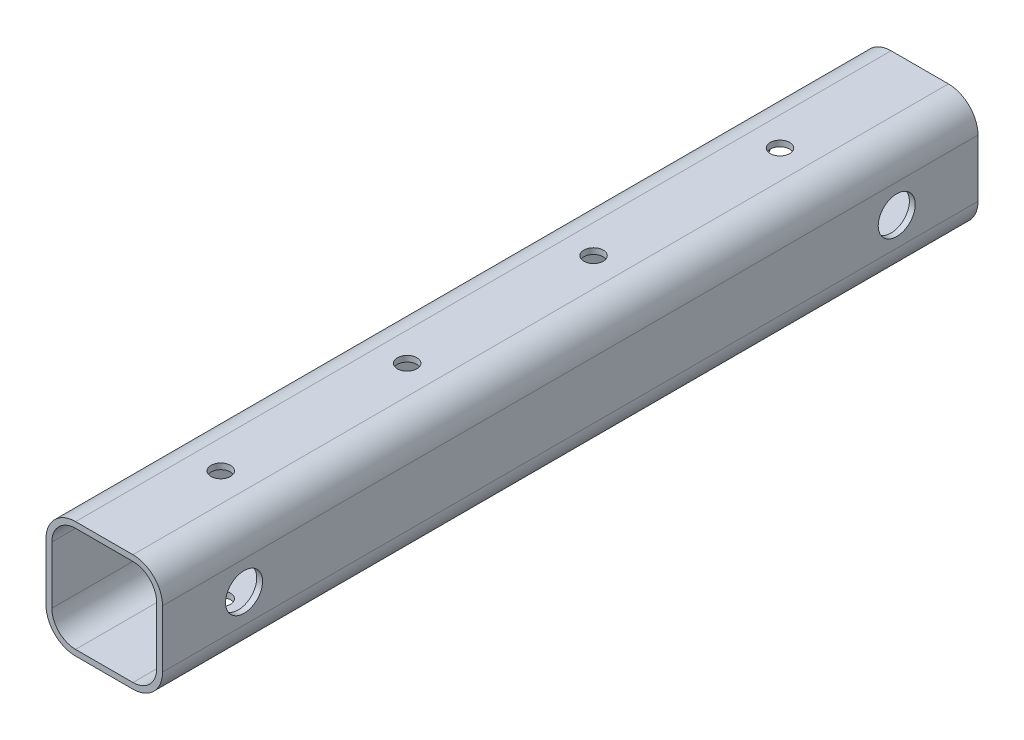
SolidWorks part; units mm, degrees
ref_plane "Alzado" through (0, 0, 0) normal (0, 0, 1) x (1, 0, 0)
ref_plane "Planta" through (0, 0, 0) normal (0, 1, 0) x (1, 0, 0)
ref_plane "Vista lateral" through (0, 0, 0) normal (1, 0, 0) x (0, 0, -1)
sketch "Sketch2" plane through (0, 0, 0) normal (1, 0, 0) x (0, 0, -1)
  line L0 (0, 0) -> (350, 0)
  dimension "D1" = 350
other "Square tube 2 X 2 X 0.25(1)"
ref_plane "Plane1" through (0, 0, 0) normal (0, 0, -1) x (0, 1, 0)
sketch "Sketch15" plane through (0, 0, 0) normal (0, 0, -1) x (0, 1, 0)
  line L0 (-12.3, -22.5) -> (12.3, -22.5)
  line L1 (-22.5, -12.3) -> (-22.5, 12.3)
  line L2 (12.3, 22.5) -> (-12.3, 22.5)
  line L3 (22.5, 12.3) -> (22.5, -12.3)
  line L4 (-12.3, -25) -> (12.3, -25)
  line L5 (-25, -12.3) -> (-25, 12.3)
  line L6 (12.3, 25) -> (-12.3, 25)
  line L7 (25, 12.3) -> (25, -12.3)
  line L8 (0, 0) -> (22.5, 0) construction
  line L9 (0, 0) -> (0, 22.5) construction
  arc A0 (25, 12.3) -> (12.3, 25) centre (12.3, 12.3) ccw
  arc A1 (12.3, -25) -> (25, -12.3) centre (12.3, -12.3) ccw
  arc A2 (-25, -12.3) -> (-12.3, -25) centre (-12.3, -12.3) ccw
  arc A3 (-12.3, 25) -> (-25, 12.3) centre (-12.3, 12.3) ccw
  arc A4 (-12.3, 22.5) -> (-22.5, 12.3) centre (-12.3, 12.3) ccw
  arc A5 (22.5, 12.3) -> (12.3, 22.5) centre (12.3, 12.3) ccw
  arc A6 (12.3, -22.5) -> (22.5, -12.3) centre (12.3, -12.3) ccw
  arc A7 (-22.5, -12.3) -> (-12.3, -22.5) centre (-12.3, -12.3) ccw
  point P3 (0, 25)
  point P4 (25, 0)
  point P5 (0, -25)
  point P6 (-25, 0)
  point P7 (-25, 25)
  point P8 (-25, -25)
  point P33 (0, 0)
  point P35 (25, -25)
  point P36 (25, 25)
  point P37 (0, 0)
  dimension "D1" = 12.7
  dimension "Thickness" = 2.5
  dimension "V_leg" = 50
sketch "Sketch16" plane through (-25, 0, 0) normal (-1, 0, 0) x (0, 0, 1)
  line L0 (0, 25) -> (-50.8, 25)
  line L1 (-50.8, 25) -> (-50.8, -25)
  line L2 (-50.8, -25) -> (0, -25)
  line L3 (0, -25) -> (0, 25)
  line L4 (0, 0) -> (-350, 0) construction
  line L5 (-350, -12.3) -> (-350, 12.3) construction
  circle A0 centre (-35, 0) radius 7.9375
  dimension "D1" = 35
extrude "Cut-Extrude1" cut sketch "Sketch16" against normal up to surface (50 mm away) contours A0 up to face at (25, 0, -175)
sketch "Sketch18" plane through (-25, 0, 0) normal (-1, 0, 0) x (0, 0, 1)
  line L0 (-350.1134, -25) -> (-299.3134, -25) construction
  line L1 (-299.3134, -25) -> (-299.3134, 25) construction
  line L2 (-299.3134, 25) -> (-350.1134, 25) construction
  line L3 (-350.1134, 25) -> (-350.1134, -25) construction
  line L4 (-350.1134, 0) -> (0, 0) construction
  line L8 (0, -12.3) -> (0, 12.3)
  line L9 (0, 12.3) -> (-350, 12.3)
  line L10 (-350, 12.3) -> (-350, -12.3)
  line L11 (-350, -12.3) -> (0, -12.3)
  line L12 (0, -12.3) -> (0, 12.3)
  line L13 (0, 12.3) -> (-350, 12.3) construction
  line L14 (-350, 12.3) -> (-350, -12.3) construction
  line L15 (-350, -12.3) -> (0, -12.3) construction
  circle A0 centre (-315.1134, 0) radius 7.9375
  dimension "D2" = 35
  dimension "D1" = 0
extrude "Cut-Extrude2" cut sketch "Sketch18" against normal up to surface (50 mm away) contours A0 up to face at (25, 0, -27.0625)
sketch "Sketch19" plane through (0, 25, 0) normal (0, 1, 0) x (-1, 0, 0)
  line L0 (12.3, -350) -> (-12.3, -350) construction
  line L4 (12.3, -350) -> (-12.3, -350)
  line L5 (0, -350) -> (0, -332.6531)
  line L6 (10.215, -350) -> (10.215, 0) construction
  line L11 (-10.215, 0) -> (-10.215, -350) construction
  line L17 (12.3, 0) -> (-12.3, 0)
  line L18 (12.3, -350) -> (12.3, 0) construction
  line L19 (-12.3, -350) -> (12.3, -350) construction
  line L20 (-12.3, 0) -> (-12.3, -350) construction
  circle A0 centre (0, -290) radius 4.1672
  circle A1 centre (0, -210) radius 4.1672
  circle A2 centre (0, -130) radius 4.1672
  circle A3 centre (0, -50) radius 4.1672
  arc A105 (7, -50) -> (-7, -50) centre (0, -50) ccw construction
  arc A106 (7, -50) -> (-7, -50) centre (0, -50) ccw
  arc A107 (7, -130) -> (-7, -130) centre (0, -130) ccw construction
  arc A108 (7, -130) -> (-7, -130) centre (0, -130) ccw
  arc A109 (7, -210) -> (-7, -210) centre (0, -210) ccw construction
  arc A110 (7, -210) -> (-7, -210) centre (0, -210) ccw
  arc A111 (7, -290) -> (-7, -290) centre (0, -290) ccw construction
  arc A112 (7, -290) -> (-7, -290) centre (0, -290) ccw
  arc A117 (-7, -290) -> (7, -290) centre (0, -290) ccw construction
  arc A118 (-7, -290) -> (7, -290) centre (0, -290) ccw
  arc A119 (-7, -210) -> (7, -210) centre (0, -210) ccw construction
  arc A120 (-7, -210) -> (7, -210) centre (0, -210) ccw
  arc A121 (-7, -130) -> (7, -130) centre (0, -130) ccw construction
  arc A122 (-7, -130) -> (7, -130) centre (0, -130) ccw
  arc A123 (-7, -50) -> (7, -50) centre (0, -50) ccw construction
  arc A124 (-7, -50) -> (7, -50) centre (0, -50) ccw
  dimension "D1" = 8.3344
  dimension "D2" = 8.3344
  dimension "D3" = 8.3344
  dimension "D4" = 8.3344
extrude "Cut-Extrude3" cut sketch "Sketch19" against normal up to surface (50 mm away) contours A109 A119 | A111 A117 | A107 A121 | A105 A123 | A0 | A1 | A2 | A3 | A118 A112
